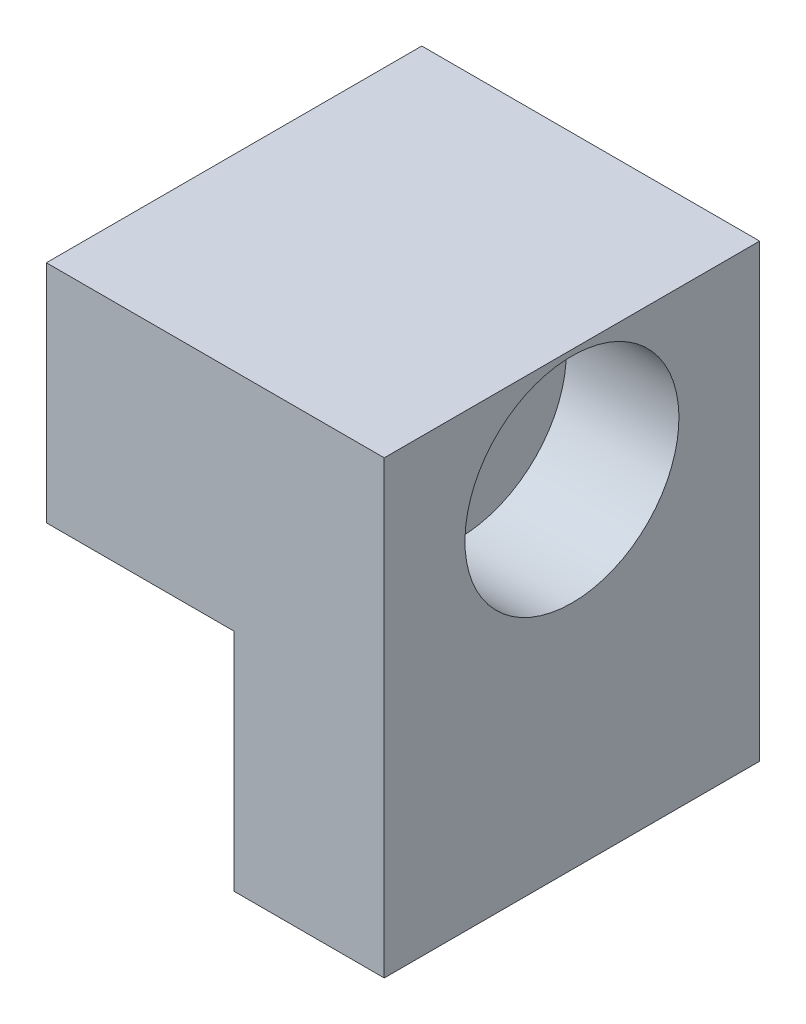
SolidWorks part; units mm, degrees
ref_plane "Front Plane" through (0, 0, 0) normal (0, 0, 1) x (1, 0, 0)
ref_plane "Top Plane" through (0, 0, 0) normal (0, 1, 0) x (1, 0, 0)
ref_plane "Right Plane" through (0, 0, 0) normal (1, 0, 0) x (0, 0, -1)
sketch "Sketch1" plane through (0, 0, 0) normal (0, 0, 1) x (1, 0, 0)
  line L0 (0, 0) -> (9, 0)
  line L1 (9, 0) -> (9, -12)
  line L2 (9, -12) -> (5, -12)
  line L3 (5, -12) -> (5, -6)
  line L4 (5, -6) -> (0, -6)
  line L5 (0, -6) -> (0, 0)
  dimension "D1" = 6
  dimension "D2" = 5
  dimension "D3" = 4
  dimension "D4" = 6
extrude "Boss-Extrude1" add sketch "Sketch1" along normal blind 10
ref_plane "Plane1" through (0, -3, 0) normal (0, 1, 0) x (1, 0, 0)
sketch "Sketch4" plane through (0, -3, 0) normal (0, 1, 0) x (1, 0, 0)
  line L0 (0, -5) -> (9, -5)
  line L1 (0, -10) -> (0, 0) construction
  line L2 (9, -10) -> (9, 0) construction
  line L4 (6, -3.725) -> (6, -2.15)
  line L5 (6, -3.725) -> (0, -3.725)
  line L6 (0, -5) -> (0, -3.725)
  line L7 (9, -5) -> (9, -2.15)
  line L8 (6, -2.15) -> (9, -2.15)
  dimension "D1" = 2.85
  dimension "D2" = 1.275
  dimension "D3" = 3
revolve "Cut-Revolve2" cut sketch "Sketch4" angle 360 about L0
